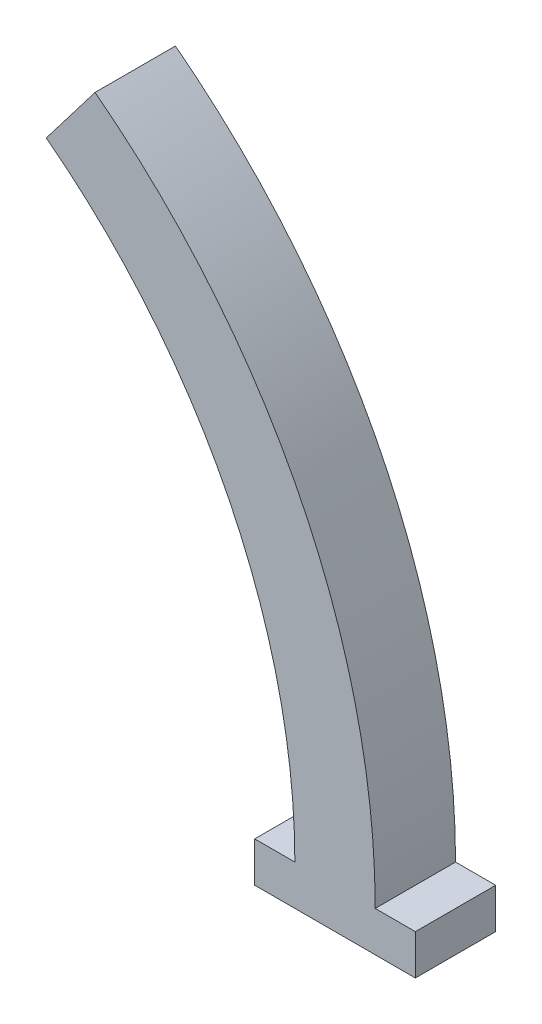
SolidWorks part; units mm, degrees
ref_plane "Front Plane" through (0, 0, 0) normal (0, 0, 1) x (1, 0, 0)
ref_plane "Top Plane" through (0, 0, 0) normal (0, 1, 0) x (1, 0, 0)
ref_plane "Right Plane" through (0, 0, 0) normal (1, 0, 0) x (0, 0, -1)
sketch "Sketch1" plane through (0, 0, 0) normal (0, 1, 0) x (1, 0, 0)
  line L1 (0, 0) -> (10.16, 0)
  line L2 (0, 0) -> (0, 5.08)
  line L3 (0, 5.08) -> (10.16, 5.08)
  line L4 (10.16, 0) -> (10.16, 5.08)
  dimension "D1" = 5.08
  dimension "D2" = 10.16
extrude "Boss-Extrude1" add sketch "Sketch1" along normal blind 2.54
sketch "Sketch4" plane through (0, 0, 0) normal (0, 0, -1) x (-1, 0, 0)
  line L0 (-7.62, 2.54) -> (37.4877, 2.54) construction
  line L2 (-7.62, 2.54) -> (-10.16, 2.54) construction
  arc A0 (-7.62, 2.54) -> (10.0953, 38.378) centre (37.4877, 2.54) cw
  point P2 (10.0953, 38.378)
  dimension "D1" = 2.54
extrude "Extrude-Thin1" add sketch "Sketch4" along normal blind 5.08 thin
